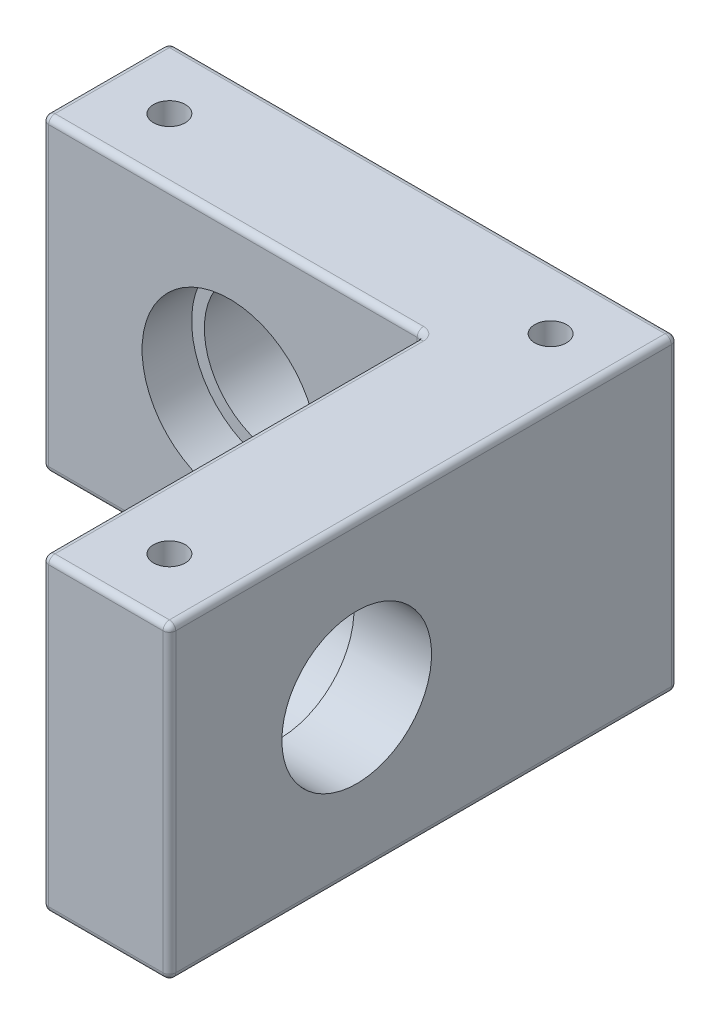
SolidWorks part; units mm, degrees
ref_plane "Front Plane" through (0, 0, 0) normal (0, 0, 1) x (1, 0, 0)
ref_plane "Top Plane" through (0, 0, 0) normal (0, 1, 0) x (1, 0, 0)
ref_plane "Right Plane" through (0, 0, 0) normal (1, 0, 0) x (0, 0, -1)
sketch "Sketch2" plane through (0, 0, 0) normal (0, 1, 0) x (1, 0, 0)
  line L0 (0, 0) -> (0, 101.6)
  line L1 (0, 101.6) -> (-101.6, 101.6)
  line L2 (-101.6, 101.6) -> (-101.6, 76.2)
  line L3 (-101.6, 76.2) -> (-25.4, 76.2)
  line L4 (-25.4, 76.2) -> (-25.4, 0)
  line L5 (-25.4, 0) -> (0, 0)
  dimension "D1" = 101.6
  dimension "D2" = 101.6
  dimension "D3" = 25.4
  dimension "D4" = 25.4
extrude "Boss-Extrude1" add sketch "Sketch2" along normal blind 61.722
sketch "Sketch3" plane through (0, 0, -76.2) normal (0, 0, 1) x (1, 0, 0)
  line L1 (-101.6, 0) -> (-25.4, 0) construction
  line L2 (-25.4, 61.722) -> (-25.4, 0) construction
  circle A0 centre (-64.1604, 30.861) radius 17.5006
  dimension "D3" = 35.0012
  dimension "D1" = 38.7604
  dimension "D2" = 30.861
extrude "Cut-Extrude1" cut sketch "Sketch3" against normal blind 9.906
sketch "Sketch4" plane through (0, 0, -86.106) normal (0, 0, 1) x (1, 0, 0)
  circle A0 centre (-64.1604, 30.861) radius 14.9606
  dimension "D1" = 29.9212
extrude "Cut-Extrude2" cut sketch "Sketch4" against normal through all
sketch "Sketch5" plane through (0, 61.722, 0) normal (0, 1, 0) x (1, 0, 0)
  line L0 (0, 101.6) -> (-101.6, 101.6) construction
  line L1 (0, 0) -> (0, 101.6) construction
  line L2 (-101.6, 101.6) -> (-101.6, 76.2) construction
  line L3 (-25.4, 0) -> (0, 0) construction
  circle A0 centre (-88.9, 88.9) radius 3.175
  circle A1 centre (-12.7, 88.9) radius 3.175
  circle A2 centre (-12.7, 12.7) radius 3.175
  dimension "D1" = 6.35
  dimension "D2" = 6.35
  dimension "D3" = 6.35
  dimension "D4" = 12.7
  dimension "D5" = 12.7
  dimension "D6" = 12.7
  dimension "D7" = 12.7
  dimension "D8" = 12.7
  dimension "D9" = 12.7
extrude "Cut-Extrude3" cut sketch "Sketch5" against normal through all
sketch "Sketch6" plane through (-25.4, 0, 0) normal (-1, 0, 0) x (0, 0, 1)
  line L1 (-76.2, 0) -> (0, 0) construction
  line L2 (-76.2, 61.722) -> (-76.2, 0) construction
  circle A0 centre (-37.4396, 30.861) radius 17.5006
  dimension "D3" = 35.0012
  dimension "D1" = 38.7604
  dimension "D2" = 30.861
extrude "Cut-Extrude4" cut sketch "Sketch6" against normal blind 9.906
sketch "Sketch7" plane through (-15.494, 0, 0) normal (-1, 0, 0) x (0, 0, 1)
  circle A0 centre (-37.4396, 30.861) radius 14.9606
  dimension "D1" = 29.9212
extrude "Cut-Extrude5" cut sketch "Sketch7" against normal through all
fillet "Fillet1" radius 1.27 18 edges at (-25.4, 30.861, 0) (-12.7, 61.722, 0) (0, 30.861, 0) (-12.7, 0, 0) (-101.6, 30.861, -101.6) (-101.6, 61.722, -88.9) (-101.6, 30.861, -76.2) (-101.6, 0, -88.9) (0, 0, -50.8) (0, 30.861, -101.6) (-50.8, 0, -101.6) (-25.4, 0, -38.1) (-63.5, 0, -76.2) (-50.8, 61.722, -101.6) (0, 61.722, -50.8) (-25.4, 61.722, -38.1) (-63.5, 61.722, -76.2) (-25.4, 30.861, -76.2)
